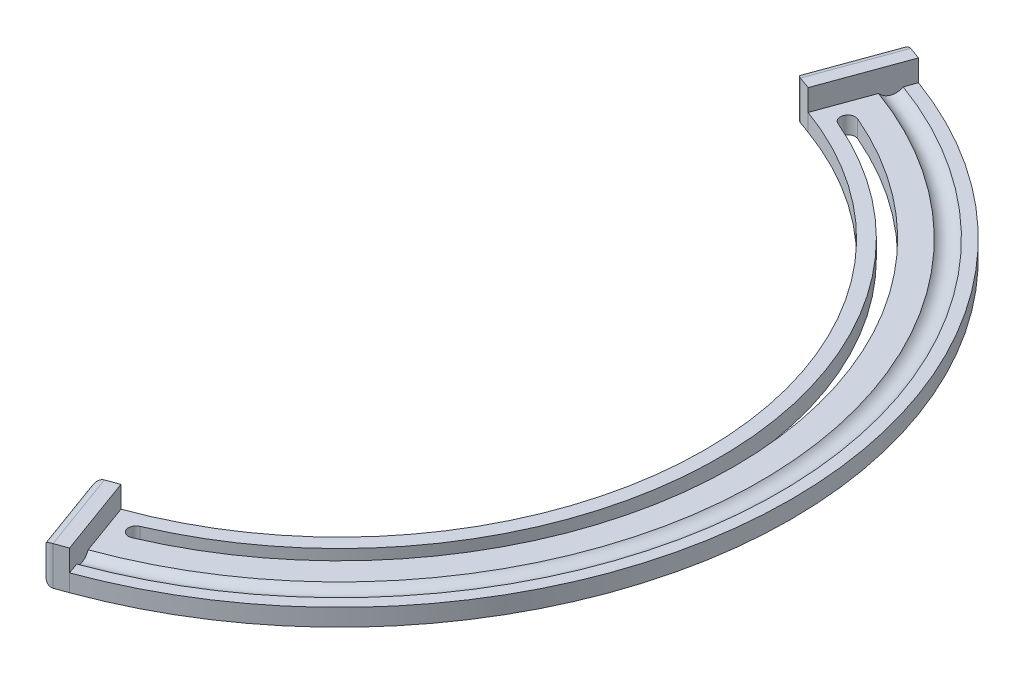
SolidWorks part; units mm, degrees
ref_plane "前视基准面" through (0, 0, 0) normal (0, 0, 1) x (1, 0, 0)
ref_plane "上视基准面" through (0, 0, 0) normal (0, 1, 0) x (1, 0, 0)
ref_plane "右视基准面" through (0, 0, 0) normal (1, 0, 0) x (0, 0, -1)
sketch "草图1" plane through (0, 0, 0) normal (0, 1, 0) x (1, 0, 0)
  line L0 (0, 0) -> (98.6677, -35.9121)
  line L1 (0, 0) -> (98.6677, 35.9121)
  line L2 (0, 0) -> (105, 0) construction
  line L3 (0, 0) -> (52.5, -90.9327)
  line L4 (0, 0) -> (52.5, 90.9327)
  circle A0 centre (0, 0) radius 100
  circle A1 centre (0, 0) radius 105
  circle A2 centre (0, 0) radius 95
  dimension "D1" = 200
  dimension "D2" = 210
  dimension "D3" = 190
  dimension "D4" = 20
  dimension "D5" = 20
  dimension "D6" = 60
  dimension "D7" = 60
sketch "草图2" plane through (0, 0, 0) normal (0, 0, 1) x (1, 0, 0)
  line L0 (0, 0) -> (100, 0) construction
  line L1 (0, 0) -> (98.6677, 0) construction
  line L2 (100, 0) -> (100, -8) construction
  line L3 (95, 2) -> (105, 2)
  line L4 (95, 2) -> (95, -2)
  line L5 (95, -2) -> (105, -2)
  line L6 (105, 2) -> (105, -2)
  line L7 (95, 2) -> (105, -2) construction
  line L8 (95, -2) -> (105, 2) construction
  line L9 (95, -6) -> (105, -6)
  line L10 (95, -6) -> (95, -10)
  line L11 (95, -10) -> (105, -10)
  line L12 (105, -6) -> (105, -10)
  line L13 (95, -6) -> (105, -10) construction
  line L14 (95, -10) -> (105, -6) construction
  line L15 (95, -3) -> (95, -2)
  line L16 (96.5, -3) -> (103.5, -3)
  line L17 (96.5, -3) -> (96.5, -5)
  line L18 (96.5, -5) -> (103.5, -5)
  line L19 (103.5, -3) -> (103.5, -5)
  line L20 (96.5, -3) -> (103.5, -5) construction
  line L21 (96.5, -5) -> (103.5, -3) construction
  line L22 (95, -3) -> (105, -3)
  line L23 (95, -3) -> (95, -5)
  line L24 (95, -5) -> (105, -5)
  line L25 (105, -3) -> (105, -5)
  line L26 (95, -3) -> (105, -5) construction
  line L27 (95, -5) -> (105, -3) construction
  line L28 (95, -2) -> (96.5, -2)
  line L29 (96.5, -2) -> (96.5, -3)
  line L30 (95, -6) -> (85, -6)
  line L31 (85, -6) -> (85, -10)
  line L32 (85, -10) -> (95, -10)
  line L36 (103.5, -3) -> (103.5, -2)
  line L37 (103.5, -2) -> (105, -2)
  line L38 (105, -2) -> (105, -3)
  line L39 (95, 2) -> (95, 4)
  line L40 (95, 4) -> (85, 4)
  line L41 (85, 4) -> (85, 7)
  line L42 (85, 7) -> (105, 7)
  line L43 (105, 7) -> (105, 2)
  line L44 (0, 24.3669) -> (0, -24.3669) construction
  circle A0 centre (100, -4) radius 3
  point P11 (100, -8)
  point P40 (0, 0)
  dimension "D7" = 6
  dimension "D1" = 100
  dimension "D2" = 10
  dimension "D3" = 4
  dimension "D4" = 4
  dimension "D5" = 4
  dimension "D6" = 10
  dimension "D8" = 7
  dimension "D9" = 10
  dimension "D10" = 2
  dimension "D11" = 2
  dimension "D12" = 1
  dimension "D13" = 10
  dimension "D14" = 1
  dimension "D16" = 5
  dimension "D17" = 3
  dimension "D18" = 20
revolve "旋转1" add sketch "草图2" angle 140 mid plane about L44
sketch "草图3" plane through (0, 0, 0) normal (-0.9397, 0, 0.342) x (0.342, 0, 0.9397)
  line L0 (85, -6) -> (85, -1)
  line L1 (85, -1) -> (105, -1)
  line L2 (105, -1) -> (105, -6)
  line L5 (97.7639, -6) -> (85, -6)
  line L6 (85, -6) -> (85, -10)
  line L7 (85, -10) -> (105, -10)
  line L8 (105, -10) -> (105, -6)
  line L9 (105, -6) -> (102.2361, -6)
  line L10 (97.7639, -6) -> (85, -6)
  line L12 (85, -10) -> (105, -10)
  line L13 (105, -10) -> (105, -6)
  line L14 (105, -6) -> (102.2361, -6)
  line L18 (85, -6) -> (85, -10)
  arc A1 (97.7639, -6) -> (102.2361, -6) centre (100, -4) ccw
  arc A2 (97.7639, -6) -> (102.2361, -6) centre (100, -4) ccw
  dimension "D2" = 5
  dimension "D1" = 0
extrude "凸台-拉伸1" add sketch "草图3" along normal blind 5
sketch "草图4" plane through (0, 0, 0) normal (-0.9397, 0, -0.342) x (-0.342, 0, 0.9397)
  line L0 (-105, -6) -> (-105, -1)
  line L1 (-105, -1) -> (-85, -1)
  line L2 (-85, -1) -> (-85, -6)
  line L5 (-102.2361, -6) -> (-105, -6)
  line L6 (-105, -6) -> (-105, -10)
  line L7 (-105, -10) -> (-85, -10)
  line L8 (-85, -10) -> (-85, -6)
  line L9 (-85, -6) -> (-97.7639, -6)
  line L10 (-102.2361, -6) -> (-105, -6)
  line L11 (-105, -6) -> (-105, -10)
  line L12 (-105, -10) -> (-85, -10)
  line L14 (-85, -6) -> (-97.7639, -6)
  line L18 (-85, -10) -> (-85, -6)
  arc A1 (-102.2361, -6) -> (-97.7639, -6) centre (-100, -4) ccw
  arc A2 (-102.2361, -6) -> (-97.7639, -6) centre (-100, -4) ccw
  dimension "D2" = 5
  dimension "D1" = 0
extrude "凸台-拉伸2" add sketch "草图4" along normal blind 5
sketch "草图5" plane through (0, -6, 0) normal (0, 1, 0) x (1, 0, 0)
  line L0 (29.0717, 79.8739) -> (33.4372, 91.868) construction
  line L1 (29.0717, -79.8739) -> (35.9121, -98.6677) construction
  circle A0 centre (35.4327, 82.7316) radius 1.75
  circle A1 centre (35.4327, -82.7316) radius 1.75
  circle A2 centre (0, 0) radius 90
  circle A3 centre (0, 0) radius 88.25
  circle A4 centre (0, 0) radius 91.75
  dimension "D1" = 3.5
  dimension "D2" = 3.5
  dimension "D3" = 180
  dimension "D4" = 5
  dimension "5" = 5
extrude "切除-拉伸1" cut sketch "草图5" against normal blind 5 contours A2 A0 | A0 A2 | A1 A4 A0 A2 | A3 A1 A2 A0 | A1 A2 | A2 A1
fillet "圆角1" radius 2 8 edges at (27.7935, -1, -90.9809) (24.3732, -5.5, -81.584) (27.7935, -10, -90.9809) (31.2137, -5.5, -100.3778) (27.7935, -1, 90.9809) (31.2137, -5.5, 100.3778) (27.7935, -10, 90.9809) (24.3732, -5.5, 81.584)
